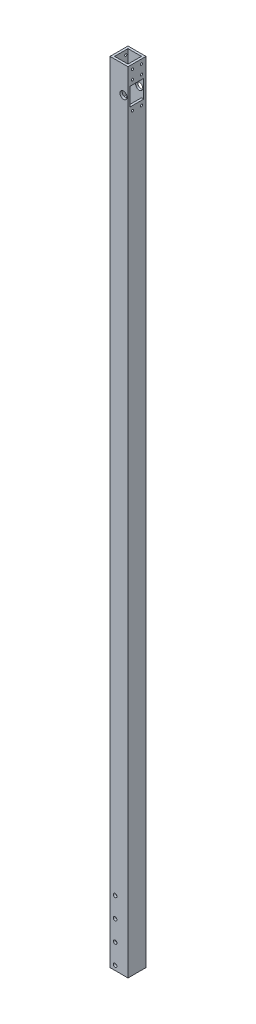
SolidWorks part; units mm, degrees
material "6061 Alloy"
ref_plane "Front" through (0, 0, 0) normal (0, 0, 1) x (1, 0, 0)
ref_plane "Top" through (0, 0, 0) normal (0, 1, 0) x (1, 0, 0)
ref_plane "Right" through (0, 0, 0) normal (1, 0, 0) x (0, 0, -1)
sketch "Sketch1" plane through (0, 0, 0) normal (0, 1, 0) x (1, 0, 0)
  line L1 (-9.525, 9.525) -> (9.525, 9.525)
  line L2 (-9.525, 9.525) -> (-9.525, -9.525)
  line L3 (-9.525, -9.525) -> (9.525, -9.525)
  line L4 (9.525, 9.525) -> (9.525, -9.525)
  line L5 (-9.525, 9.525) -> (9.525, -9.525) construction
  line L6 (-9.525, -9.525) -> (9.525, 9.525) construction
  line L7 (-12.7, 12.7) -> (12.7, 12.7)
  line L8 (-12.7, 12.7) -> (-12.7, -12.7)
  line L9 (-12.7, -12.7) -> (12.7, -12.7)
  line L10 (12.7, 12.7) -> (12.7, -12.7)
  line L11 (-12.7, 12.7) -> (12.7, -12.7) construction
  line L12 (-12.7, -12.7) -> (12.7, 12.7) construction
  point P0 (0, 0)
  point P6 (0, 0)
  dimension "D1" = 3.175
  dimension "D2" = 3.175
  dimension "D3" = 25.4
  dimension "D4" = 25.4
extrude "Boss-Extrude1" add sketch "Sketch1" along normal blind 1117.6
sketch "Sketch2" plane through (12.7, 0, 0) normal (1, 0, 0) x (0, 0, -1)
  line L0 (-12.7, 1117.6) -> (-12.7, 0) construction
  line L1 (-9.525, 1092.2) -> (9.525, 1092.2)
  line L2 (-9.525, 1092.2) -> (-9.525, 1066.8)
  line L3 (-9.525, 1066.8) -> (9.525, 1066.8)
  line L4 (9.525, 1092.2) -> (9.525, 1066.8)
  line L5 (12.7, 1117.6) -> (12.7, 0) construction
  line L6 (-12.7, 1117.6) -> (12.7, 1117.6) construction
  dimension "D1" = 3.175
  dimension "D2" = 3.175
  dimension "D3" = 25.4
  dimension "D4" = 25.4
extrude "Cut-Extrude1" cut sketch "Sketch2" against normal up to next
hole_wizard "3/8 Clearance Hole1" positions "Sketch3" profile "Sketch4" hole size "3/8" standard "ANSI Inch" end condition through all
sketch "Sketch3" plane through (0, 0, 12.7) normal (0, 0, 1) x (1, 0, 0)
  line L0 (12.7, 1092.2) -> (12.7, 1066.8) construction
  line L2 (6.35, 1079.5) -> (12.7, 1079.5) construction
  point P0 (6.35, 1079.5)
  dimension "D1" = 6.35
sketch "Sketch4" plane through (6.35, 1079.5, 12.7) normal (1, 0, 0) x (0, -1, 0)
  line L0 (0, 0) -> (0, 25.4)
  line L1 (0, 25.4) -> (5.0419, 25.4)
  line L2 (5.0419, 25.4) -> (5.0419, 0)
  line L5 (5.0419, 0) -> (0, 0)
  line L11 (0, -6.35) -> (0, 107.95) construction
  dimension "Thru Hole Dia." = 10.0838
  dimension "Thru Hole Depth" = 25.4
hole_wizard "#10 Clearance Hole1" positions "Sketch5" profile "Sketch6" hole size "#10" standard "ANSI Inch"
sketch "Sketch5" plane through (-12.7, -56.3791, -922.0473) normal (-1, 0, 0) x (0, 0, 1)
  point P0 (922.0473, 138.9291)
  point P2 (922.0473, 113.5291)
  point P4 (922.0473, 69.0791)
sketch "Sketch6" plane through (-12.7, 82.55, 0) normal (0, 1, 0) x (0, 0, 1)
  line L0 (0, 0) -> (0, 4.7078)
  line L1 (0, 4.7078) -> (2.5527, 3.174)
  line L2 (2.5527, 3.174) -> (2.5527, 0)
  line L3 (2.5527, 0) -> (0, 0)
  line L4 (0, 4.7078) -> (-2.5527, 3.174) construction
  line L5 (0, -6.35) -> (0, 107.95) construction
  dimension "Hole Dia." = 5.1054
  dimension "Hole Depth" = 3.174
  dimension "Drill Angle" = 118
hole_wizard "1/8 (0.125) Diameter Hole1" positions "Sketch7" profile "Sketch8" hole size "1/8" standard "ANSI Inch" end condition through all
sketch "Sketch7" plane through (12.7, 0, 0) normal (1, 0, 0) x (0, 0, -1)
  line L0 (0, 1117.6) -> (0, 1104.9) construction
  line L1 (-12.7, 1117.6) -> (12.7, 1117.6) construction
  line L2 (0, 1104.9) -> (-12.7, 1104.9) construction
  line L3 (-12.7, 1117.6) -> (-12.7, 0) construction
  line L6 (-6.35, 1111.25) -> (6.35, 1111.25) construction
  line L7 (-6.35, 1111.25) -> (-6.35, 1098.55) construction
  line L8 (-6.35, 1098.55) -> (6.35, 1098.55) construction
  line L9 (6.35, 1111.25) -> (6.35, 1098.55) construction
  line L10 (-6.35, 1111.25) -> (6.35, 1098.55) construction
  line L11 (-6.35, 1098.55) -> (6.35, 1111.25) construction
  line L12 (0, 1098.55) -> (0, 1060.45) construction
  line L14 (-6.35, 1060.45) -> (6.35, 1060.45) construction
  point P11 (6.35, 1098.55)
  point P36 (-6.35, 1111.25)
  point P37 (-6.35, 1098.55)
  point P38 (6.35, 1111.25)
  point P44 (-6.35, 1060.45)
  point P45 (6.35, 1060.45)
  dimension "D1" = 12.7
  dimension "D2" = 38.1
sketch "Sketch8" plane through (12.7, 1060.45, -6.35) normal (0, 1, 0) x (0, 0, -1)
  line L0 (0, 0) -> (0, 25.4)
  line L1 (0, 25.4) -> (1.5875, 25.4)
  line L2 (1.5875, 25.4) -> (1.5875, 0)
  line L5 (1.5875, 0) -> (0, 0)
  line L11 (0, -6.35) -> (0, 107.95) construction
  dimension "Thru Hole Dia." = 3.175
  dimension "Thru Hole Depth" = 25.4
hole_wizard "#10 Clearance Hole2" positions "Sketch9" profile "Sketch10" hole size "#10" standard "ANSI Inch" end condition through all
sketch "Sketch9" plane through (0, 0, 12.7) normal (0, 0, 1) x (1, 0, 0)
  point P0 (112.945, 382.3635)
  point P2 (-5.5562, 6.35)
  point P5 (-5.5562, 34.925)
  point P14 (-5.5562, 92.075)
  point P19 (-5.5562, 63.5)
sketch "Sketch10" plane through (112.945, 382.3635, 12.7) normal (1, 0, 0) x (0, -1, 0)
  line L0 (0, 0) -> (0, 25.4)
  line L1 (0, 25.4) -> (2.5527, 25.4)
  line L2 (2.5527, 25.4) -> (2.5527, 0)
  line L5 (2.5527, 0) -> (0, 0)
  line L11 (0, -6.35) -> (0, 107.95) construction
  dimension "Thru Hole Dia." = 5.1054
  dimension "Thru Hole Depth" = 25.4
